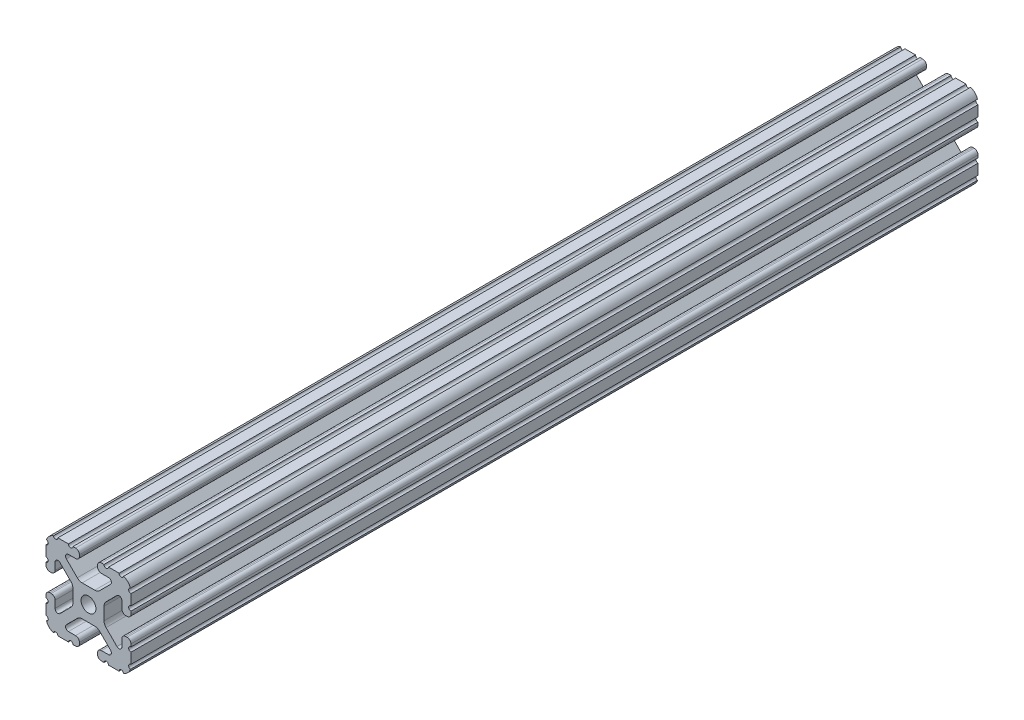
SolidWorks part; units mm, degrees
ref_plane "Front Plane" through (0, 0, 0) normal (0, 0, 1) x (1, 0, 0)
ref_plane "Top Plane" through (0, 0, 0) normal (0, 1, 0) x (1, 0, 0)
ref_plane "Right Plane" through (0, 0, 0) normal (1, 0, 0) x (0, 0, -1)
sketch "Sketch2" plane through (0, 0, 0) normal (0, 0, 1) x (1, 0, 0)
  line L0 (0, 19.05) -> (0, -19.05) construction
  line L1 (-19.05, 0) -> (19.05, 0) construction
  line L2 (4.064, -19.05) -> (19.05, -19.05)
  line L3 (19.05, -19.05) -> (19.05, -4.064)
  line L4 (4.064, -19.05) -> (4.064, -14.986)
  line L5 (4.064, -14.986) -> (12.1123, -14.986)
  line L6 (12.1123, -14.986) -> (4.1113, -6.985)
  line L7 (0, 0) -> (19.05, -19.05) construction
  line L8 (19.05, -4.064) -> (14.986, -4.064)
  line L9 (14.986, -4.064) -> (14.986, -12.1123)
  line L10 (14.986, -12.1123) -> (6.985, -4.1113)
  circle A0 centre (0, 0) radius 3.3274
  arc A1 (8.9963, -14.986) -> (9.909, -12.7826) centre (8.9963, -13.6953) ccw construction
  point P8 (0, -6.985)
  dimension "Center Hole Diameter" = 6.6548
  dimension "Rail Height" = 38.1
  dimension "Rail Width" = 38.1
  dimension "T-Slot Width" = 8.128
  dimension "Slot Inner Width" = 20.574
  dimension "Thickness" = 4.064
  dimension "Slot Depth" = 8.001
  dimension "D1" = 4.064
sketch "Sketch3" plane through (0, 0, 0) normal (1, 0, 0) x (0, 0, -1)
  line L0 (-190, -19.05) -> (190, -19.05) construction
  line L1 (-164.6, 0) -> (164.6, 0) construction
  dimension "Length" = 380
  dimension "D1" = 25.4
sketch "Sketch4" plane through (0, 0, 0) normal (0, 0, 1) x (1, 0, 0)
  line L0 (5.7912, -19.05) -> (14.3002, -19.05)
  line L1 (4.064, -19.05) -> (19.05, -19.05) construction
  line L2 (4.064, -19.05) -> (4.064, -14.986) construction
  line L3 (4.064, -14.986) -> (12.1123, -14.986) construction
  line L4 (4.064, -16.7132) -> (4.064, -17.3228)
  line L5 (5.7912, -14.986) -> (8.9963, -14.986)
  line L6 (0, -6.985) -> (2.833, -6.985)
  line L7 (12.1123, -14.986) -> (4.1113, -6.985) construction
  line L8 (5.0152, -7.8889) -> (9.909, -12.7826)
  line L9 (19.05, -19.05) -> (19.05, -4.064) construction
  line L10 (14.986, -12.1123) -> (6.985, -4.1113) construction
  line L11 (14.986, -4.064) -> (14.986, -12.1123) construction
  line L12 (14.986, -8.9963) -> (14.986, -5.7912)
  line L13 (19.05, -4.064) -> (14.986, -4.064) construction
  line L14 (16.7132, -4.064) -> (17.3228, -4.064)
  line L15 (19.05, -5.7912) -> (19.05, -14.3002)
  line L16 (12.7826, -9.909) -> (7.8889, -5.0152)
  line L17 (6.985, 0) -> (6.985, -2.833)
  line L18 (-19.05, 0) -> (19.05, 0) construction
  line L19 (0, -6.985) -> (0, -3.3274)
  line L20 (0, 19.05) -> (0, -19.05) construction
  line L21 (6.985, 0) -> (3.3274, 0)
  arc A0 (4.064, -17.3228) -> (5.7912, -19.05) centre (5.7912, -17.3228) ccw
  arc A2 (4.064, -16.7132) -> (5.7912, -14.986) centre (5.7912, -16.7132) cw
  arc A3 (8.9963, -14.986) -> (9.909, -12.7826) centre (8.9963, -13.6953) ccw
  arc A4 (2.833, -6.985) -> (5.0152, -7.8889) centre (2.833, -10.0711) cw
  arc A5 (14.3002, -19.05) -> (19.05, -14.3002) centre (14.3002, -14.3002) ccw
  arc A6 (12.7826, -9.909) -> (14.986, -8.9963) centre (13.6953, -8.9963) ccw
  arc A7 (14.986, -5.7912) -> (16.7132, -4.064) centre (16.7132, -5.7912) cw
  arc A8 (17.3228, -4.064) -> (19.05, -5.7912) centre (17.3228, -5.7912) cw
  arc A9 (7.8889, -5.0152) -> (6.985, -2.833) centre (10.0711, -2.833) cw
  circle A10 centre (0, 0) radius 3.3274 construction
  arc A11 (0, -3.3274) -> (3.3274, 0) centre (0, 0) ccw
  dimension "D1" = 4.7498
  dimension "D2" = 3.0861
  dimension "D3" = 1.7272
extrude "Boss-Extrude1" add sketch "Sketch4" along normal mid plane 380
sketch "Sketch5" plane through (0, 0, 0) normal (0, 0, 1) x (1, 0, 0)
  line L0 (4.064, -19.05) -> (19.05, -19.05) construction
  line L1 (5.7912, -14.986) -> (8.9963, -14.986) construction
  line L3 (0, 0) -> (19.05, -19.05) construction
  line L4 (8.9963, -14.986) -> (8.9963, -19.05) construction
  line L5 (12.1123, -14.986) -> (4.1113, -6.985) construction
  circle A0 centre (14.7395, -19.05) radius 1.016
  circle A1 centre (7.9803, -19.05) radius 1.016
  circle A2 centre (19.05, -14.7395) radius 1.016
  circle A3 centre (19.05, -7.9803) radius 1.016
  point P10 (7.3938, -14.986)
  point P12 (13.6953, -8.9963)
  dimension "D1" = 2.032
extrude "Cut-Extrude1" cut sketch "Sketch5" against normal through all both and the other way through all
mirror "Mirror1" about plane through (0, 0, 0) normal (1, 0, 0) of bodies 137 134
mirror "Mirror2" about plane through (0, 0, 0) normal (0, 1, 0) of bodies 135
equation "\"D1@Boss-Extrude1\"=\"Length@Sketch3\""
equation "\"D1@Sketch2\"=\"Thickness@Sketch2\""
equation "\"D2@Sketch4\"=\"Slot Inner Width@Sketch2\"*0.15"
equation "\"D1@Sketch4\"=\"D3@Sketch4\"*2.75"
equation "\"D3@Sketch4\"=\"Thickness@Sketch2\"*0.425"
equation "\"D1@Sketch5\"=\"Thickness@Sketch2\"*0.5"
